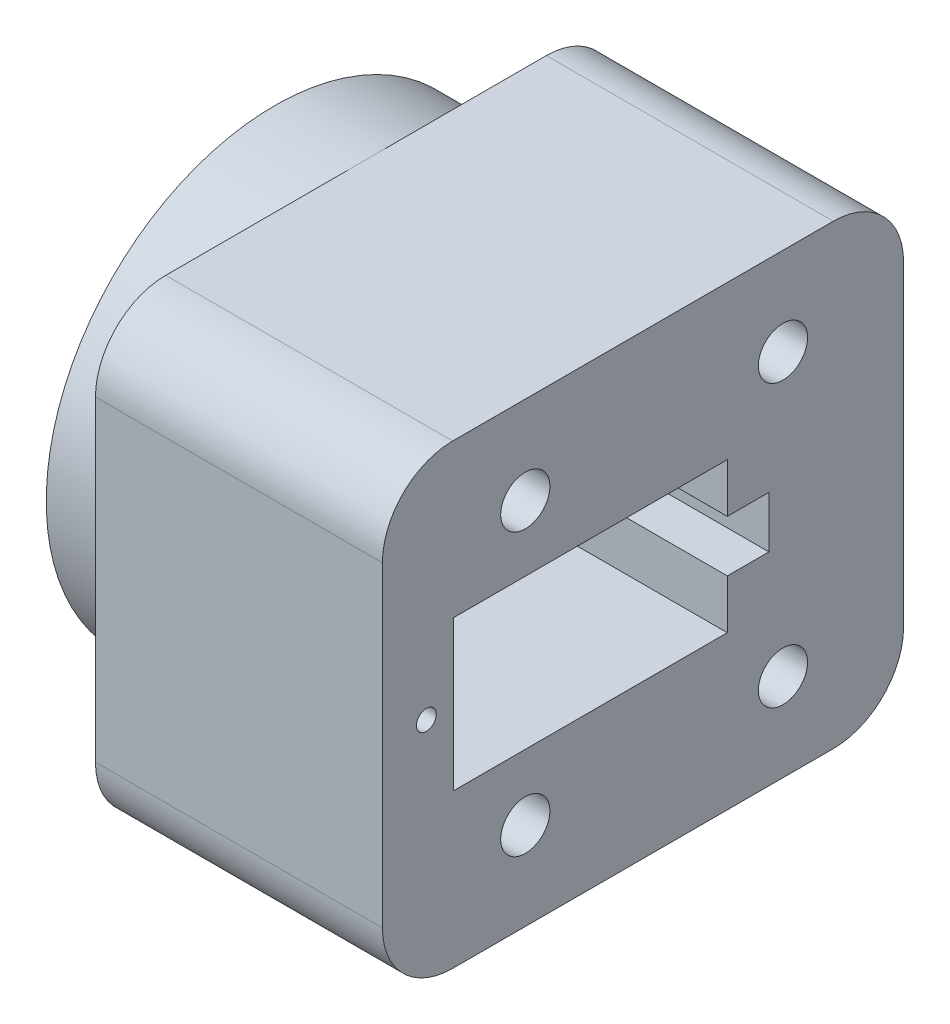
SolidWorks part; units mm, degrees
ref_plane "Front Plane" through (0, 0, 0) normal (0, 0, 1) x (1, 0, 0)
ref_plane "Top Plane" through (0, 0, 0) normal (0, 1, 0) x (1, 0, 0)
ref_plane "Right Plane" through (0, 0, 0) normal (1, 0, 0) x (0, 0, -1)
ref_plane "Plane1" through (169.4, 0, 0) normal (1, 0, 0) x (0, 0, -1)
sketch "Sketch1" plane through (169.4, 0, 0) normal (1, 0, 0) x (0, 0, -1)
  line L1 (-324.2, -8.5) -> (-283.5, -8.5)
  line L2 (-324.2, -8.5) -> (-324.2, 8.5)
  line L3 (-324.2, 8.5) -> (-283.5, 8.5)
  line L4 (-283.5, -8.5) -> (-283.5, 8.5)
extrude "Boss-Extrude1" add sketch "Sketch1" along normal blind 24.5
ref_plane "Plane2" through (189.9, 0, 0) normal (1, 0, 0) x (0, 0, -1)
sketch "Sketch2" plane through (189.9, 0, 0) normal (1, 0, 0) x (0, 0, -1)
  line L1 (-324.2, -17) -> (-283.5, -17)
  line L2 (-324.2, -17) -> (-324.2, 17)
  line L3 (-324.2, 17) -> (-283.5, 17)
  line L4 (-283.5, -17) -> (-283.5, 17)
extrude "Boss-Extrude2" add sketch "Sketch2" along normal blind 4
sketch "Sketch3" plane through (169.4, 0, 0) normal (1, 0, 0) x (0, 0, -1)
  circle A0 centre (-301, 0) radius 3.6
extrude "Cut-Extrude1" cut sketch "Sketch3" along normal blind 4.4
sketch "Sketch4" plane through (169.4, 0, 0) normal (1, 0, 0) x (0, 0, -1)
  line L0 (-285.15, -1.95) -> (-301, -2.8)
  line L1 (-301, -2.8) -> (-316.85, -1.95)
  line L2 (-316.85, -1.95) -> (-316.85, 1.95)
  line L3 (-316.85, 1.95) -> (-301, 2.8)
  line L4 (-301, 2.8) -> (-285.15, 1.95)
  line L5 (-285.15, 1.95) -> (-285.15, -1.95)
extrude "Cut-Extrude2" cut sketch "Sketch4" along normal blind 4.4
sketch "Sketch5" plane through (169.4, 0, 0) normal (1, 0, 0) x (0, 0, -1)
  circle A0 centre (-301, 0) radius 1.2
extrude "Cut-Extrude3" cut sketch "Sketch5" along normal blind 7
ref_plane "Plane3" through (194.5, 0, 0) normal (1, 0, 0) x (0, 0, -1)
sketch "Sketch6" plane through (194.5, 0, 0) normal (1, 0, 0) x (0, 0, -1)
  line L1 (-318.15, -6.4) -> (-294.75, -6.4)
  line L2 (-318.15, -6.4) -> (-318.15, 6.4)
  line L3 (-318.15, 6.4) -> (-294.75, 6.4)
  line L4 (-294.75, -6.4) -> (-294.75, 6.4)
extrude "Cut-Extrude4" cut sketch "Sketch6" against normal blind 19.2
sketch "Sketch7" plane through (194.5, 0, 0) normal (1, 0, 0) x (0, 0, -1)
  line L1 (-294.9, -2.2) -> (-291.2, -2.2)
  line L2 (-294.9, -2.2) -> (-294.9, 2.2)
  line L3 (-294.9, 2.2) -> (-291.2, 2.2)
  line L4 (-291.2, -2.2) -> (-291.2, 2.2)
extrude "Cut-Extrude5" cut sketch "Sketch7" against normal blind 16
sketch "Sketch8" plane through (194.5, 0, 0) normal (1, 0, 0) x (0, 0, -1)
  circle A0 centre (-320.45, 0) radius 0.85
extrude "Cut-Extrude6" cut sketch "Sketch8" against normal blind 8.6
sketch "Sketch9" plane through (194.5, 0, 0) normal (1, 0, 0) x (0, 0, -1)
  circle A0 centre (-290, 12) radius 1.7
  circle A1 centre (-290, -12) radius 1.7
  circle A2 centre (-312, 12) radius 1.7
  circle A3 centre (-312, -12) radius 1.7
extrude "Cut-Extrude7" cut sketch "Sketch9" against normal blind 4.7
ref_plane "Plane4" through (0, 0, 283) normal (0, 0, 1) x (1, 0, 0)
sketch "Sketch10" plane through (0, 0, 283) normal (0, 0, 1) x (1, 0, 0)
  line L1 (178.5, -2.2) -> (184, -2.2)
  line L2 (178.5, -2.2) -> (178.5, 2.2)
  line L3 (178.5, 2.2) -> (184, 2.2)
  line L4 (184, -2.2) -> (184, 2.2)
extrude "Cut-Extrude8" cut sketch "Sketch10" along normal blind 8.3
sketch "Sketch11" plane through (169.4, 0, 0) normal (1, 0, 0) x (0, 0, -1)
  line L0 (-279.7, -19.5) -> (-324.2, -19.5)
  line L1 (-324.2, -19.5) -> (-324.2, -8.5)
  line L2 (-324.2, -8.5) -> (-283.5, -8.5)
  line L3 (-283.5, -8.5) -> (-283.5, 8.5)
  line L4 (-283.5, 8.5) -> (-324.2, 8.5)
  line L5 (-324.2, 8.5) -> (-324.2, 19.5)
  line L6 (-324.2, 19.5) -> (-279.7, 19.5)
  line L7 (-279.7, 19.5) -> (-279.7, -19.5)
extrude "Boss-Extrude3" add sketch "Sketch11" along normal blind 24.5
sketch "Sketch12" plane through (0, 0, 283) normal (0, 0, 1) x (1, 0, 0)
  line L1 (178.5, -2.2) -> (184, -2.2)
  line L2 (178.5, -2.2) -> (178.5, 2.2)
  line L3 (178.5, 2.2) -> (184, 2.2)
  line L4 (184, -2.2) -> (184, 2.2)
extrude "Cut-Extrude9" cut sketch "Sketch12" along normal mid plane 7
sketch "Sketch13" plane through (169.4, 0, 0) normal (1, 0, 0) x (0, 0, -1)
  line L0 (-324.2, 13.5) -> (-325.5, 13.5)
  line L1 (-325.5, 13.5) -> (-325.5, 20.5)
  line L2 (-325.5, 20.5) -> (-318.2, 20.5)
  line L3 (-318.2, 20.5) -> (-318.2, 19.5)
  line L4 (-324.2, -13.5) -> (-325.5, -13.5)
  line L5 (-325.5, -13.5) -> (-325.5, -20.5)
  line L6 (-325.5, -20.5) -> (-318.2, -20.5)
  line L7 (-318.2, -20.5) -> (-318.2, -19.5)
  line L8 (-279.7, 13.5) -> (-278.4, 13.5)
  line L9 (-278.4, 13.5) -> (-278.4, 20.5)
  line L10 (-278.4, 20.5) -> (-285.7, 20.5)
  line L11 (-285.7, 20.5) -> (-285.7, 19.5)
  line L12 (-279.7, -13.5) -> (-278.4, -13.5)
  line L13 (-278.4, -13.5) -> (-278.4, -20.5)
  line L14 (-278.4, -20.5) -> (-285.7, -20.5)
  line L15 (-285.7, -20.5) -> (-285.7, -19.5)
  arc A0 (-318.2, 19.5) -> (-324.2, 13.5) centre (-318.2, 13.5) ccw
  arc A1 (-318.2, -19.5) -> (-324.2, -13.5) centre (-318.2, -13.5) cw
  arc A2 (-285.7, 19.5) -> (-279.7, 13.5) centre (-285.7, 13.5) cw
  arc A3 (-285.7, -19.5) -> (-279.7, -13.5) centre (-285.7, -13.5) ccw
extrude "Cut-Extrude10" cut sketch "Sketch13" along normal through all
sketch "Sketch14" plane through (169.4, 0, 0) normal (1, 0, 0) x (0, 0, -1)
  circle A0 centre (-301, 0) radius 19.5
  circle A1 centre (-301, 0) radius 18.3
extrude "Boss-Extrude4" add sketch "Sketch14" against normal blind 7.9
sketch "Sketch15" plane through (194.5, 0, 0) normal (1, 0, 0) x (0, 0, -1)
  circle A0 centre (-290, 12) radius 2.1
  circle A1 centre (-290, -12) radius 2.1
  circle A2 centre (-312, 12) radius 2.1
  circle A3 centre (-312, -12) radius 2.1
extrude "Cut-Extrude11" cut sketch "Sketch15" against normal blind 6.1
sketch "Sketch16" plane through (169.4, 0, 0) normal (1, 0, 0) x (0, 0, -1)
  circle A0 centre (-301, 0) radius 18.3
  circle A1 centre (-301, 0) radius 17.7
extrude "Boss-Extrude6" add sketch "Sketch16" against normal blind 6
